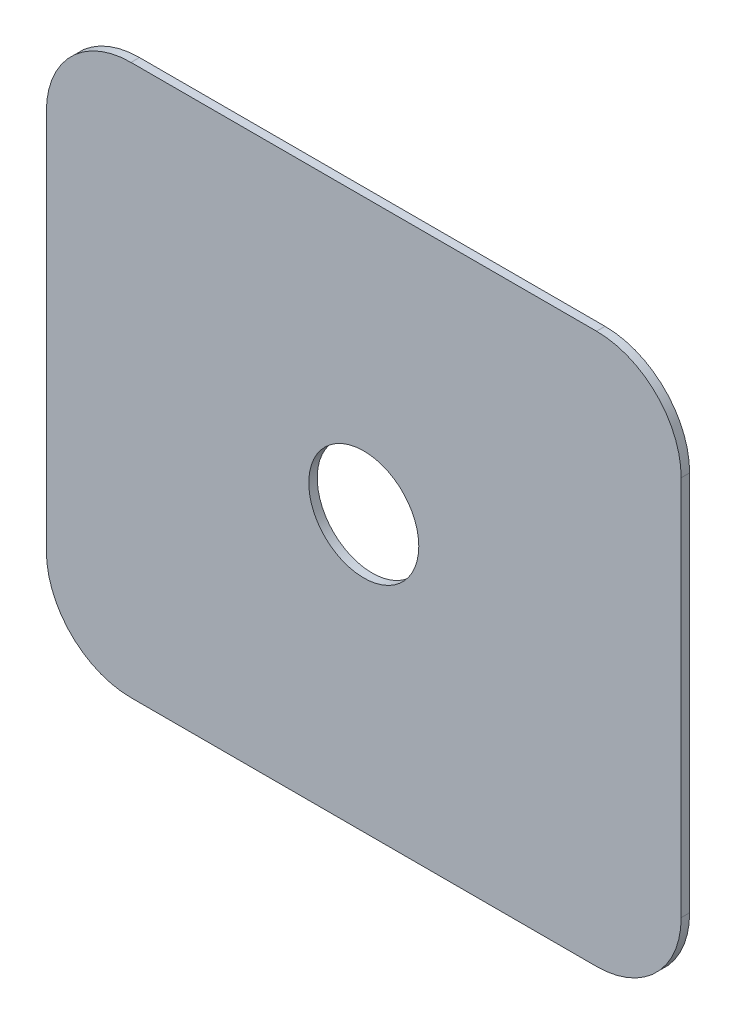
SolidWorks part; units mm, degrees
ref_plane "前视基准面" through (0, 0, 0) normal (0, 0, 1) x (1, 0, 0)
ref_plane "上视基准面" through (0, 0, 0) normal (0, 1, 0) x (1, 0, 0)
ref_plane "右视基准面" through (0, 0, 0) normal (1, 0, 0) x (0, 0, -1)
other "Configuration Table"
sketch "草图1" plane through (0, 0, 0) normal (0, 0, 1) x (1, 0, 0)
  line L1 (-75, 65) -> (75, 65)
  line L2 (-75, 65) -> (-75, -65)
  line L3 (-75, -65) -> (75, -65)
  line L4 (75, 65) -> (75, -65)
  line L5 (-75, 65) -> (75, -65) construction
  line L6 (-75, -65) -> (75, 65) construction
  circle A0 centre (0, 0) radius 13
  point P0 (0, 0)
  dimension "D3" = 26
  dimension "D1" = 130
  dimension "D2" = 150
extrude "凸台-拉伸1" add sketch "草图1" along normal blind 2
fillet "圆角1" radius 20 4 edges at (75, -65, 1) (75, 65, 1) (-75, -65, 1) (-75, 65, 1)
